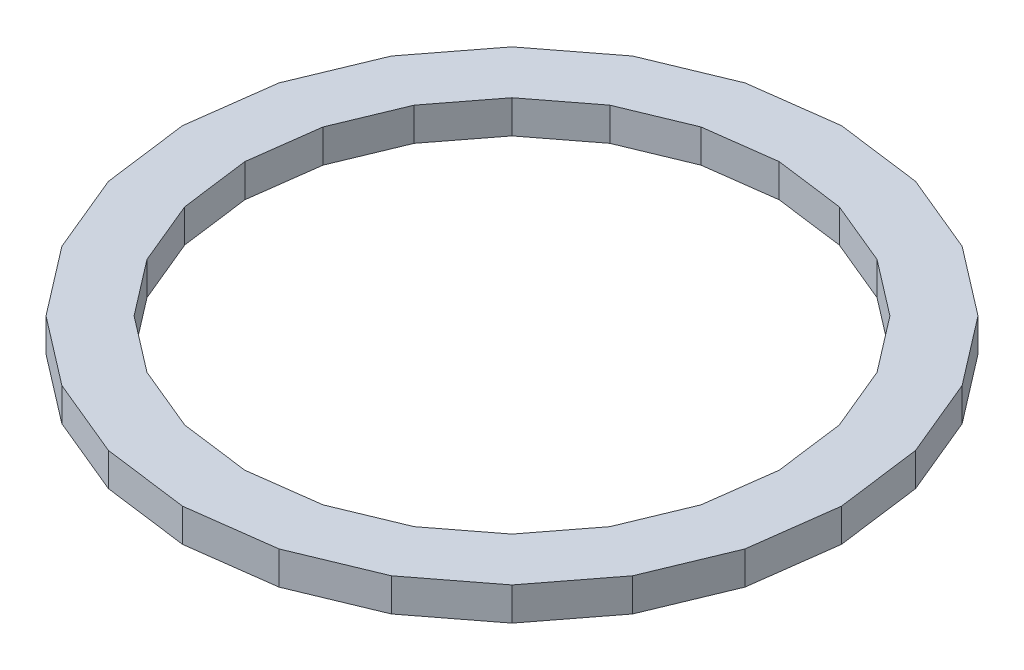
SolidWorks part; units mm, degrees
ref_plane "Front Plane" through (0, 0, 0) normal (0, 0, 1) x (1, 0, 0)
ref_plane "Top Plane" through (0, 0, 0) normal (0, 1, 0) x (1, 0, 0)
ref_plane "Right Plane" through (0, 0, 0) normal (1, 0, 0) x (0, 0, -1)
sketch "Sketch2" plane through (0, 0, 0) normal (0, 1, 0) x (1, 0, 0)
  line L0 (0, 0) -> (-153.8652, 0) construction
  line L1 (-189.732, 0) -> (-183.2671, -49.1063)
  line L2 (-183.2671, -49.1063) -> (-164.3128, -94.866)
  line L3 (-164.3128, -94.866) -> (-134.1608, -134.1608)
  line L4 (-134.1608, -134.1608) -> (-94.866, -164.3128)
  line L5 (-94.866, -164.3128) -> (-49.1063, -183.2671)
  line L6 (-49.1063, -183.2671) -> (0, -189.732)
  line L7 (0, -189.732) -> (49.1063, -183.2671)
  line L8 (49.1063, -183.2671) -> (94.866, -164.3128)
  line L9 (94.866, -164.3128) -> (134.1608, -134.1608)
  line L10 (134.1608, -134.1608) -> (164.3128, -94.866)
  line L11 (164.3128, -94.866) -> (183.2671, -49.1063)
  line L12 (183.2671, -49.1063) -> (189.732, 0)
  line L13 (189.732, 0) -> (183.2671, 49.1063)
  line L14 (183.2671, 49.1063) -> (164.3128, 94.866)
  line L15 (164.3128, 94.866) -> (134.1608, 134.1608)
  line L16 (134.1608, 134.1608) -> (94.866, 164.3128)
  line L17 (94.866, 164.3128) -> (49.1063, 183.2671)
  line L18 (49.1063, 183.2671) -> (0, 189.732)
  line L19 (0, 189.732) -> (-49.1063, 183.2671)
  line L20 (-49.1063, 183.2671) -> (-94.866, 164.3128)
  line L21 (-94.866, 164.3128) -> (-134.1608, 134.1608)
  line L22 (-134.1608, 134.1608) -> (-164.3128, 94.866)
  line L23 (-164.3128, 94.866) -> (-183.2671, 49.1063)
  line L24 (-183.2671, 49.1063) -> (-189.732, 0)
  line L25 (-153.8652, 0) -> (-148.6224, -39.8232)
  line L26 (-148.6224, -39.8232) -> (-133.2512, -76.9326)
  line L27 (-133.2512, -76.9326) -> (-108.7991, -108.7991)
  line L28 (-108.7991, -108.7991) -> (-76.9326, -133.2512)
  line L29 (-76.9326, -133.2512) -> (-39.8232, -148.6224)
  line L30 (-39.8232, -148.6224) -> (0, -153.8652)
  line L31 (0, -153.8652) -> (39.8232, -148.6224)
  line L32 (39.8232, -148.6224) -> (76.9326, -133.2512)
  line L33 (76.9326, -133.2512) -> (108.7991, -108.7991)
  line L34 (108.7991, -108.7991) -> (133.2512, -76.9326)
  line L35 (133.2512, -76.9326) -> (148.6224, -39.8232)
  line L36 (148.6224, -39.8232) -> (153.8652, 0)
  line L37 (153.8652, 0) -> (148.6224, 39.8232)
  line L38 (148.6224, 39.8232) -> (133.2512, 76.9326)
  line L39 (133.2512, 76.9326) -> (108.7991, 108.7991)
  line L40 (108.7991, 108.7991) -> (76.9326, 133.2512)
  line L41 (76.9326, 133.2512) -> (39.8232, 148.6224)
  line L42 (39.8232, 148.6224) -> (0, 153.8652)
  line L43 (0, 153.8652) -> (-39.8232, 148.6224)
  line L44 (-39.8232, 148.6224) -> (-76.9326, 133.2512)
  line L45 (-76.9326, 133.2512) -> (-108.7991, 108.7991)
  line L46 (-108.7991, 108.7991) -> (-133.2512, 76.9326)
  line L47 (-133.2512, 76.9326) -> (-148.6224, 39.8232)
  line L48 (-148.6224, 39.8232) -> (-153.8652, 0)
  line L49 (-189.732, 0) -> (-153.8652, 0) construction
  circle A0 centre (0, 0) radius 188.1089 construction
  circle A1 centre (0, 0) radius 152.5489 construction
  dimension "D1" = 49.53
  dimension "D2" = 35.56
extrude "Boss-Extrude2" add sketch "Sketch2" along normal blind 19.05
